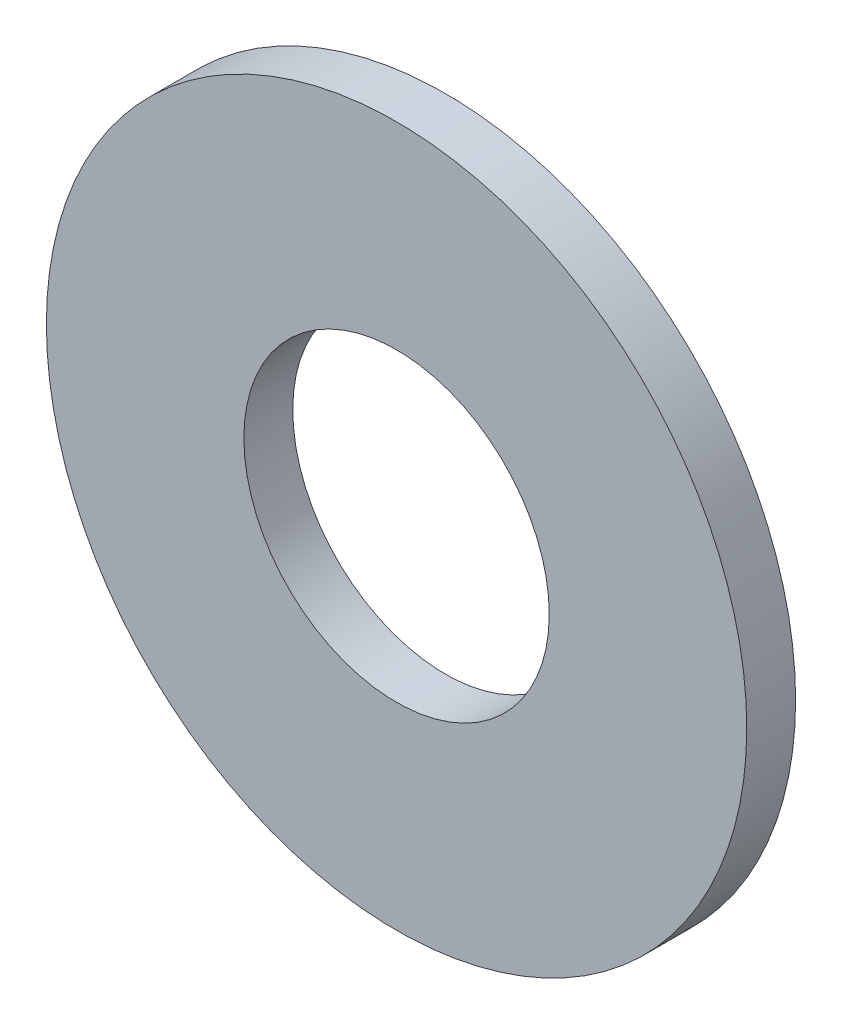
SolidWorks part; units mm, degrees
material "Q355"
ref_plane "前视基准面" through (0, 0, 0) normal (0, 0, 1) x (1, 0, 0)
ref_plane "上视基准面" through (0, 0, 0) normal (0, 1, 0) x (1, 0, 0)
ref_plane "右视基准面" through (0, 0, 0) normal (1, 0, 0) x (0, 0, -1)
sketch "草图1" plane through (0, 0, 0) normal (0, 0, 1) x (1, 0, 0)
  circle A0 centre (0, 0) radius 37.5
  circle A1 centre (0, 0) radius 86
  dimension "D1" = 172
  dimension "D2" = 75
extrude "凸台-拉伸1" add sketch "草图1" along normal blind 12
